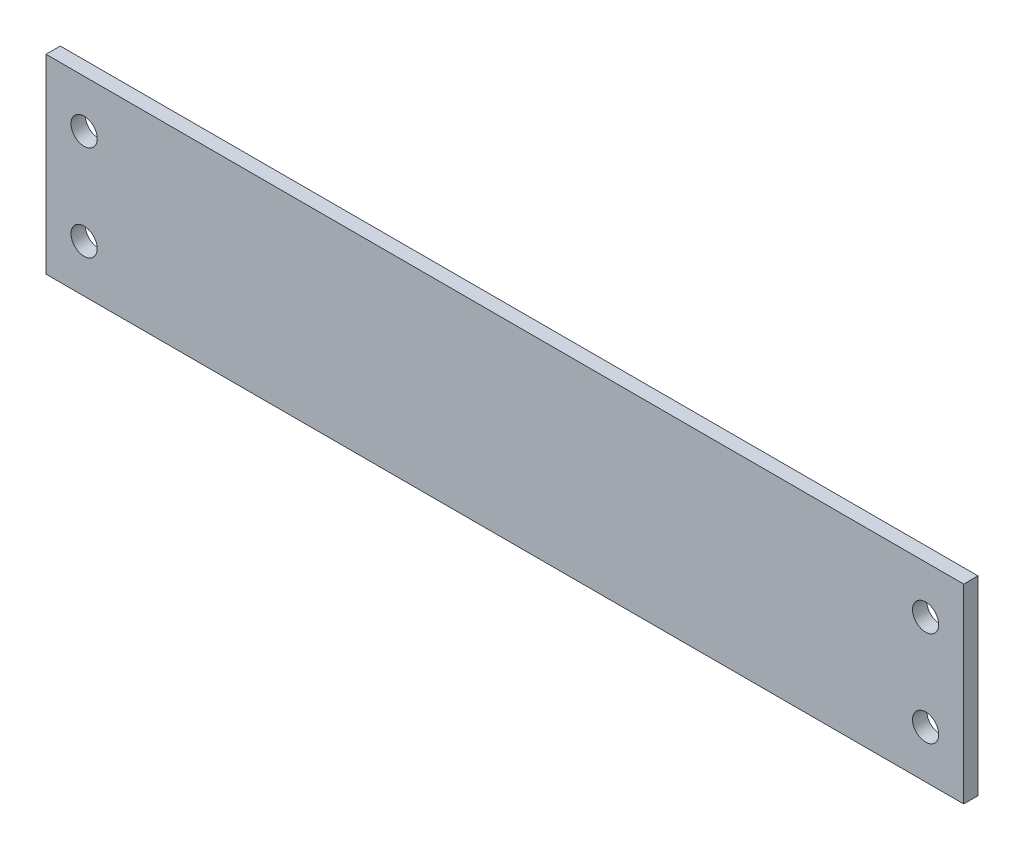
SolidWorks part; units mm, degrees
ref_plane "Front Plane" through (0, 0, 0) normal (0, 0, 1) x (1, 0, 0)
ref_plane "Top Plane" through (0, 0, 0) normal (0, 1, 0) x (1, 0, 0)
ref_plane "Right Plane" through (0, 0, 0) normal (1, 0, 0) x (0, 0, -1)
sketch "Extrusion Base Sketch" plane through (0, 0, 0) normal (0, 0, 1) x (1, 0, 0)
  line L0 (0, 40) -> (0, 0)
  line L5 (-192.75, 40) -> (0, 40)
  line L6 (-170.75, 40) -> (-170.75, 0) construction
  line L7 (-192.75, 0) -> (0, 0)
  line L8 (-22, 40) -> (-22, 0) construction
  line L9 (-192.75, 40) -> (-192.75, 0)
  line L10 (-8, 30) -> (-8, 10) construction
  line L11 (-8, 20) -> (0, 20) construction
  line L12 (-184.75, 30) -> (-184.75, 10) construction
  dimension "D3" = 40
  dimension "D1" = 148.75
  dimension "D2" = 20
extrude "Extrusion Base Extrude" add sketch "Extrusion Base Sketch" along normal blind 3
hole_wizard "M5 Mounting Holes" positions "M5 Mounting Holes Position Sketch" profile "M5 Mounting Holes Profile Sketch" hole size "M5" standard "ANSI Metric" end condition through all
sketch "M5 Mounting Holes Position Sketch" plane through (0, 0, 3) normal (0, 0, 1) x (1, 0, 0)
  point P0 (-8, 30)
  point P2 (-8, 10)
  point P4 (-184.75, 30)
  point P6 (-184.75, 10)
sketch "M5 Mounting Holes Profile Sketch" plane through (-8, 30, 3) normal (1, 0, 0) x (0, -1, 0)
  line L0 (0, 0) -> (0, 3)
  line L1 (0, 3) -> (2.75, 3)
  line L2 (2.75, 3) -> (2.75, 0)
  line L5 (2.75, 0) -> (0, 0)
  line L11 (0, -6.35) -> (0, 107.95) construction
  dimension "Thru Hole Dia." = 5.5
  dimension "Thru Hole Depth" = 3
equation "\"Total Height\"= 40mm"
equation "\"Logo Length\"= 148.75"
equation "\"D3@Extrusion Base Sketch\" = \"Total Height\""
equation "\"D1@Extrusion Base Sketch\"=\"Logo Length\""
